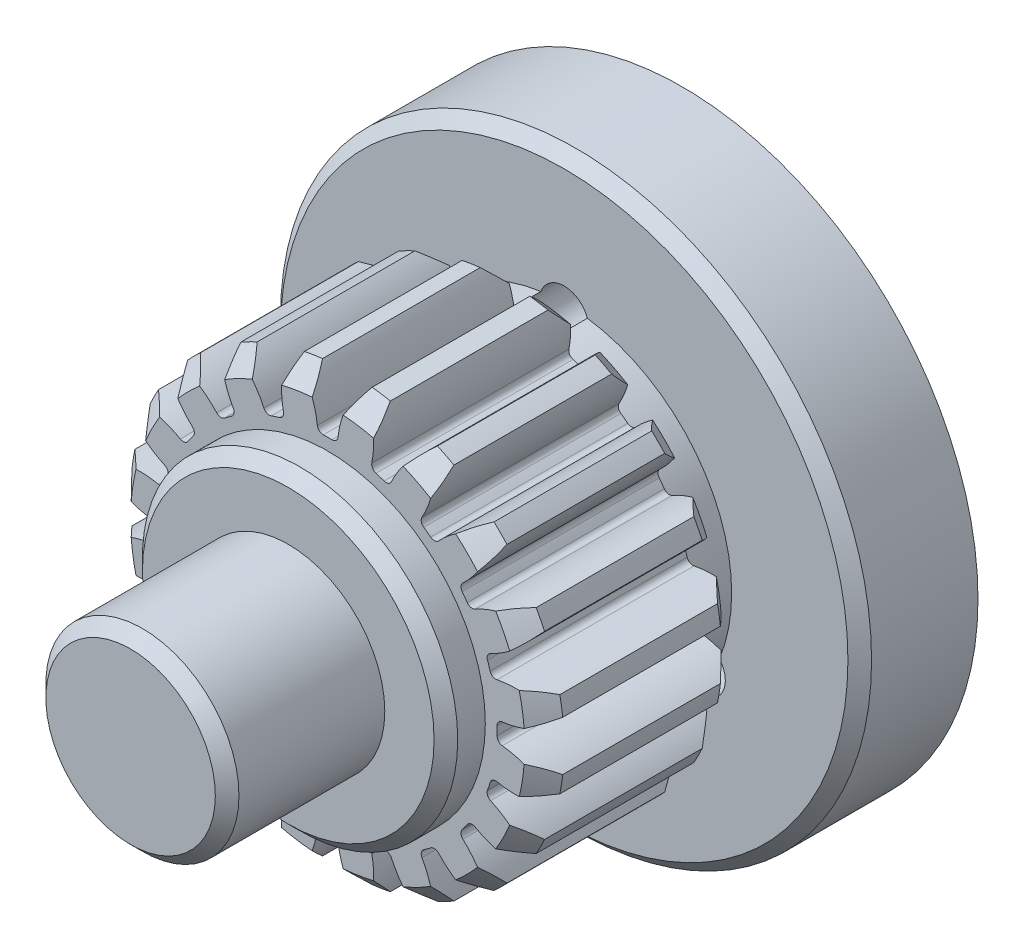
SolidWorks part; units mm, degrees
ref_plane "Front Plane" through (0, 0, 0) normal (0, 0, 1) x (1, 0, 0)
ref_plane "Top Plane" through (0, 0, 0) normal (0, 1, 0) x (1, 0, 0)
ref_plane "Right Plane" through (0, 0, 0) normal (1, 0, 0) x (0, 0, -1)
sketch "Sketch2" plane through (0, 0, 0) normal (0, 0, 1) x (1, 0, 0)
  circle A0 centre (0, 0) radius 10
  circle A1 centre (0, 0) radius 11
  circle A2 centre (0, 0) radius 8.6
  dimension "D1" = 20
  dimension "D2" = 22
  dimension "D3" = 2.4
extrude "Boss-Extrude1" add sketch "Sketch2" along normal mid plane 10 contours A1
sketch "Sketch3" plane through (0, 0, 0) normal (0, 0, 1) x (1, 0, 0)
  line L0 (0, 0) -> (0, 11) construction
  line L1 (-0.7846, 9.9692) -> (0.7846, 9.9692) construction
  line L2 (-0.499, 8.5855) -> (0, 0) construction
  line L3 (0, 7.8135) -> (-1.49, 11.9071) construction
  line L4 (0, 0) -> (1.7208, 10.8646) construction
  line L5 (0.7846, 9.9692) -> (2.3345, 9.7237) construction
  circle A0 centre (0, 0) radius 11 construction
  arc A1 (-2.0035, 11.8316) -> (-0.499, 8.5855) centre (-5.3628, 8.3028) cw
  arc A2 (2.0035, 11.8316) -> (0.499, 8.5855) centre (5.3628, 8.3028) ccw
  circle A3 centre (0, 0) radius 8.6 construction
  arc A4 (0.499, 8.5855) -> (-0.499, 8.5855) centre (0, 0) ccw
  circle A6 centre (0, 0) radius 10 construction
  circle A7 centre (0, 0) radius 12
  arc A8 (2.0035, 11.8316) -> (-2.0035, 11.8316) centre (0, 0) ccw
  circle A9 centre (0, 0) radius 11 construction
  dimension "D2" = 20
  dimension "D3" = 9
  dimension "D1" = 1
extrude "Cut-Extrude1" cut sketch "Sketch3" against normal through all both and the other way through all
fillet "Fillet1" radius 0.3 2 edges at (0.499, 8.5855, 0) (-0.499, 8.5855, 0)
chamfer "Chamfer1" distance 1 2 edges at (0, -11, -5) (0, -11, 5)
pattern_circular "CirPattern1" count 20 over 360 about axis through (0, 0, 0) along (0, 0, 1) of "Fillet1", "Cut-Extrude1"
sketch "Sketch4" plane through (0, 0, -5) normal (0, 0, -1) x (-1, 0, 0)
  circle A0 centre (0, 0) radius 8.5
  dimension "D1" = 17
extrude "Boss-Extrude2" add sketch "Sketch4" along normal blind 8
sketch "Sketch5" plane through (0, 0, -13) normal (0, 0, -1) x (-1, 0, 0)
  circle A0 centre (0, 0) radius 5.6
  dimension "D1" = 11.2
extrude "Cut-Extrude2" cut sketch "Sketch5" against normal blind 7.5
sketch "Sketch6" plane through (0, 0, 5) normal (0, 0, 1) x (1, 0, 0)
  circle A0 centre (0, 0) radius 8
  dimension "D1" = 16
extrude "Boss-Extrude3" add sketch "Sketch6" along normal blind 2
sketch "Sketch7" plane through (0, 0, 7) normal (0, 0, 1) x (1, 0, 0)
  circle A0 centre (0, 0) radius 4.9
  dimension "D1" = 9.8
extrude "Boss-Extrude4" add sketch "Sketch7" along normal blind 8
chamfer "Chamfer2" distance 0.6 angle 45 2 edges at (4.9, 0, 15) (8, 0, 7)
chamfer "Chamfer3" distance 0.6 angle 45 1 edges at (-5.6, 0, -13)
sketch "Sketch8" plane through (0, 0, -13) normal (0, 0, -1) x (-1, 0, 0)
  circle A0 centre (0, 0) radius 15
  circle A1 centre (0, 0) radius 8.5 construction
  circle A2 centre (0, 0) radius 8.5
  dimension "D1" = 30
extrude "Boss-Extrude5" add sketch "Sketch8" against normal blind 6
sketch "Sketch9" plane through (0, 0, -13) normal (0, 0, -1) x (-1, 0, 0)
  line L0 (0, -1000) -> (0, 49000) construction
  circle A0 centre (0, 8) radius 1.25
  dimension "D1" = 2.5
  dimension "D2" = 8
extrude "Cut-Extrude3" cut sketch "Sketch9" against normal blind 8
pattern_circular "CirPattern2" count 3 over 360 about axis through (0, 0, 0) along (0, 0, 1) of "Cut-Extrude3"
chamfer "Chamfer4" distance 0.6 angle 45 1 edges at (-15, 0, -7)
chamfer "Chamfer6" distance 0.4 angle 45 3 edges at (7.5532, -2.9175, -13) (-6.3032, -5.0825, -13) (-1.25, 8, -13)
equation "\"Module\"= 1mm"
equation "\"Number of Teeth\"= 20"
equation "\"D1@Sketch2\"=\"Module\" * \"Number of Teeth\""
equation "\"D2@Sketch2\"=(\"Number of Teeth\" + 2) * \"Module\""
equation "\"D3@Sketch2\"=\"Module\" * if( \"Module\" => 1.25, 2.25, 2.4) "
equation "\"D3@Sketch3\"=180deg / \"Number of Teeth\""
equation "\"D1@Fillet1\"=0.3 * \"Module\""
equation "\"D1@CirPattern1\"=\"Number of Teeth\""
equation "\"D1@Chamfer1\"=\"Module\""
equation "\"Pressure Angle\"= 20deg"
equation "\"D2@Sketch3\"=\"Pressure Angle\""
